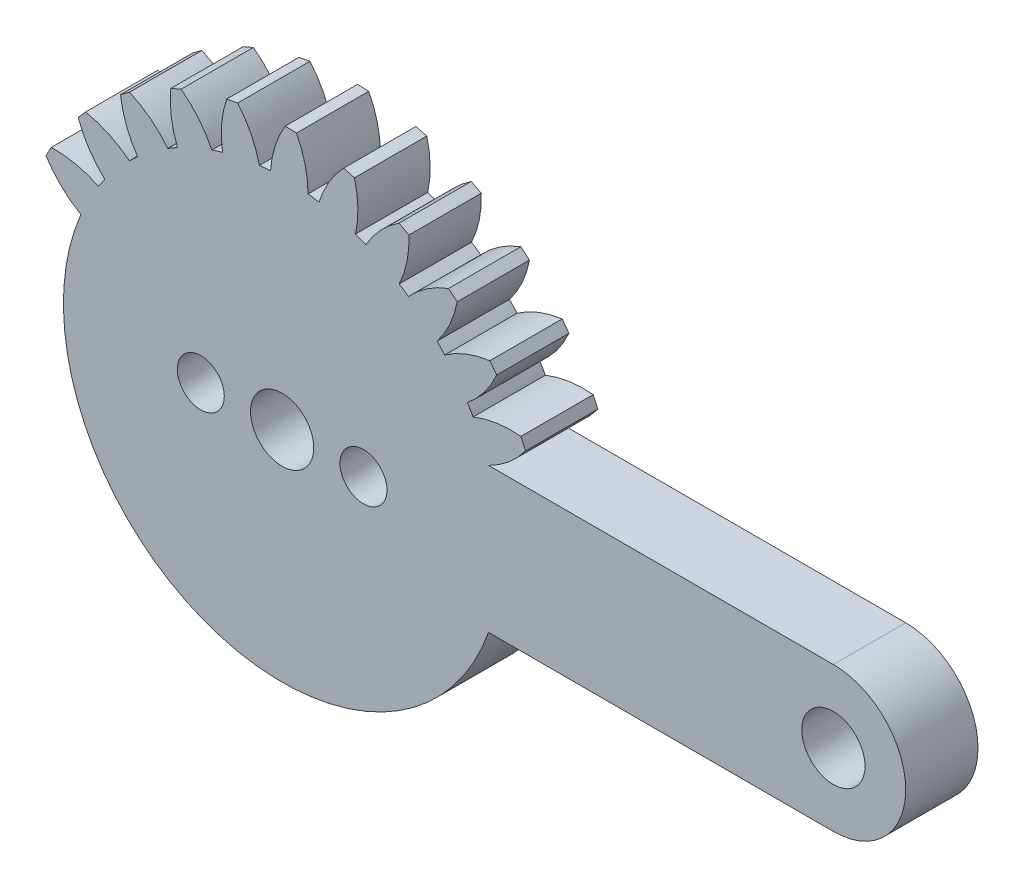
SolidWorks part; units mm, degrees
ref_plane "Front Plane" through (0, 0, 0) normal (0, 0, 1) x (1, 0, 0)
ref_plane "Top Plane" through (0, 0, 0) normal (0, 1, 0) x (1, 0, 0)
ref_plane "Right Plane" through (0, 0, 0) normal (1, 0, 0) x (0, 0, -1)
sketch "Sketch1" plane through (0, 0, 0) normal (0, 0, 1) x (1, 0, 0)
  line L0 (0, -1.75) -> (30.5, -1.75) construction
  line L1 (0, 1.75) -> (30.5, 1.75) construction
  line L2 (30.5, 1.75) -> (30.5, -1.75) construction
  line L3 (30.5, 4) -> (11.4197, 4)
  line L4 (30.5, -4) -> (11.4197, -4)
  line L5 (10.5671, 5.8946) -> (11.4197, 4) construction
  line L6 (13.2123, 6.288) -> (13.4684, 5.7189)
  line L7 (13.2123, 6.288) -> (10.8653, 5.2319) construction
  line L8 (13.4684, 5.7189) -> (11.1215, 4.6627) construction
  line L9 (11.4944, 9.0544) -> (11.8701, 8.556)
  line L10 (11.4944, 9.0544) -> (9.4392, 7.5054) construction
  line L11 (11.8701, 8.556) -> (9.8148, 7.0069) construction
  line L12 (9.2072, 11.3724) -> (9.6838, 10.9694)
  line L13 (9.2072, 11.3724) -> (7.5455, 9.4071) construction
  line L14 (9.6838, 10.9694) -> (8.0221, 9.0041) construction
  line L15 (6.4641, 13.127) -> (7.018, 12.8394)
  line L16 (6.4641, 13.127) -> (5.2781, 10.843) construction
  line L17 (7.018, 12.8394) -> (5.8321, 10.5553) construction
  line L18 (3.4007, 14.2316) -> (4.0046, 14.0736)
  line L19 (3.4007, 14.2316) -> (2.7493, 11.7418) construction
  line L20 (4.0046, 14.0736) -> (3.3532, 11.5838) construction
  line L21 (0.169, 14.6313) -> (0.7928, 14.6108)
  line L22 (0.169, 14.6313) -> (0.0844, 12.0591) construction
  line L23 (0.7928, 14.6108) -> (0.7082, 12.0386) construction
  line L24 (-3.0711, 14.3064) -> (-2.4582, 14.4243)
  line L25 (-3.0711, 14.3064) -> (-2.5847, 11.7791) construction
  line L26 (-2.4582, 14.4243) -> (-1.9718, 11.8971) construction
  line L27 (-6.1591, 13.2729) -> (-5.5875, 13.5234)
  line L28 (-6.1591, 13.2729) -> (-5.1259, 10.9158) construction
  line L29 (-5.5875, 13.5234) -> (-4.5542, 11.1663) construction
  line L30 (-8.9421, 11.582) -> (-8.44, 11.9528)
  line L31 (-8.9421, 11.582) -> (-7.4131, 9.5118) construction
  line L32 (-8.44, 11.9528) -> (-6.9111, 9.8826) construction
  line L33 (-11.2822, 9.3175) -> (-10.8746, 9.7901)
  line L34 (-11.2822, 9.3175) -> (-9.3332, 7.6367) construction
  line L35 (-10.8746, 9.7901) -> (-8.9256, 8.1094) construction
  line L36 (-13.0635, 6.5915) -> (-12.7705, 7.1426)
  line L37 (-13.0635, 6.5915) -> (-10.7911, 5.3834) construction
  line L38 (-12.7705, 7.1426) -> (-10.4981, 5.9345) construction
  line L39 (-11.1322, 4.7418) -> (11.4197, 4) construction
  arc A0 (11.4197, 4) -> (11.4197, -4) centre (0, 0) ccw
  circle A1 centre (0, 0) radius 1.75
  circle A2 centre (30.5, 0) radius 1.75
  arc A3 (30.5, -4) -> (30.5, 4) centre (30.5, 0) ccw
  arc A4 (10.5671, 5.8946) -> (13.2123, 6.288) centre (12.7001, 0.6432) cw
  arc A5 (13.4684, 5.7189) -> (11.4197, 4) centre (8.9365, 9.04) cw
  arc A6 (9.0018, 8.0857) -> (11.4944, 9.0544) centre (12.2434, 3.4361) cw
  arc A7 (11.8701, 8.556) -> (10.2523, 6.4266) centre (6.7159, 10.7926) cw
  arc A8 (6.9906, 9.8763) -> (9.2072, 11.3724) centre (11.1802, 6.0588) cw
  arc A9 (9.6838, 10.9694) -> (8.577, 8.5349) centre (4.1626, 12.0106) cw
  arc A10 (4.6332, 11.1778) -> (6.4641, 13.127) centre (9.5634, 8.3815) cw
  arc A11 (7.018, 12.8394) -> (6.477, 10.2205) centre (1.4032, 12.6338) cw
  arc A12 (2.0463, 11.9257) -> (3.4007, 14.2316) centre (7.4729, 10.289) cw
  arc A13 (4.0046, 14.0736) -> (4.0562, 11.3999) centre (-1.4257, 12.6313) cw
  arc A14 (-0.6419, 12.083) -> (0.169, 14.6313) centre (5.0122, 11.6869) cw
  arc A15 (0.7928, 14.6108) -> (1.4345, 12.0147) centre (-4.184, 12.0032) cw
  arc A16 (-3.2983, 11.6418) -> (-3.0711, 14.3064) centre (2.3034, 12.506) cw
  arc A17 (-2.4582, 14.4243) -> (-1.2582, 12.0344) centre (-6.7351, 10.7806) cw
  arc A18 (-5.7914, 10.624) -> (-6.1591, 13.2729) centre (-0.5196, 12.7058) cw
  arc A19 (-5.5875, 13.5234) -> (-3.8886, 11.4581) centre (-8.9526, 9.0241) cw
  arc A20 (-7.9977, 9.0801) -> (-8.9421, 11.582) centre (-3.3168, 12.2762) cw
  arc A21 (-8.44, 11.9528) -> (-6.3265, 10.3143) centre (-10.7267, 6.8206) cw
  arc A22 (-9.8078, 7.0864) -> (-11.2822, 9.3175) centre (-5.9497, 11.2387) cw
  arc A23 (-10.8746, 9.7901) -> (-8.451, 8.6597) centre (-11.9695, 4.2793) cw
  arc A24 (-11.1322, 4.7418) -> (-13.0635, 6.5915) centre (-8.288, 9.6445) cw
  arc A25 (-12.7705, 7.1426) -> (-10.1569, 6.5762) centre (-12.6196, 1.5261) cw
  point P103 (0, 0)
  dimension "D1" = 24.2
  dimension "D2" = 3.5
  dimension "D4" = 8
  dimension "D7" = 5.668
  dimension "D8" = 5.6185
  dimension "D3" = 30.5
  dimension "D5" = 0.6241
  dimension "D6" = 2.6742
  dimension "D9" = 2.6742
  dimension "D10" = 2.0776
  dimension "D11" = 89.999
  dimension "D12" = 11
  dimension "D13" = 22.5519
extrude "Boss-Extrude2" add sketch "Sketch1" along normal blind 4 contours L4 A3 L3 A0 A1 A2 | A13 L18 A12 A0 | A15 L21 A14 A0 | A17 L24 A16 A0 | A19 L27 A18 A0 | A21 L30 A20 A0 | A23 L33 A22 A0 | A25 L36 A24 A0 | A11 L15 A10 A0 | A9 L12 A8 A0 | A7 L9 A6 A0 | A5 L6 A4 A0
sketch "Sketch2" plane through (0, 0, 0) normal (0, 0, -1) x (-1, 0, 0)
  line L0 (-4.5, 0) -> (4.5, 0) construction
  circle A0 centre (4.5, 0) radius 1.3
  circle A1 centre (-4.5, 0) radius 1.3
  point P5 (0, 0)
  dimension "D2" = 2.6
  dimension "D1" = 9
extrude "Cut-Extrude1" cut sketch "Sketch2" against normal blind 10
ref_point "Point1"
ref_point "Point2"
